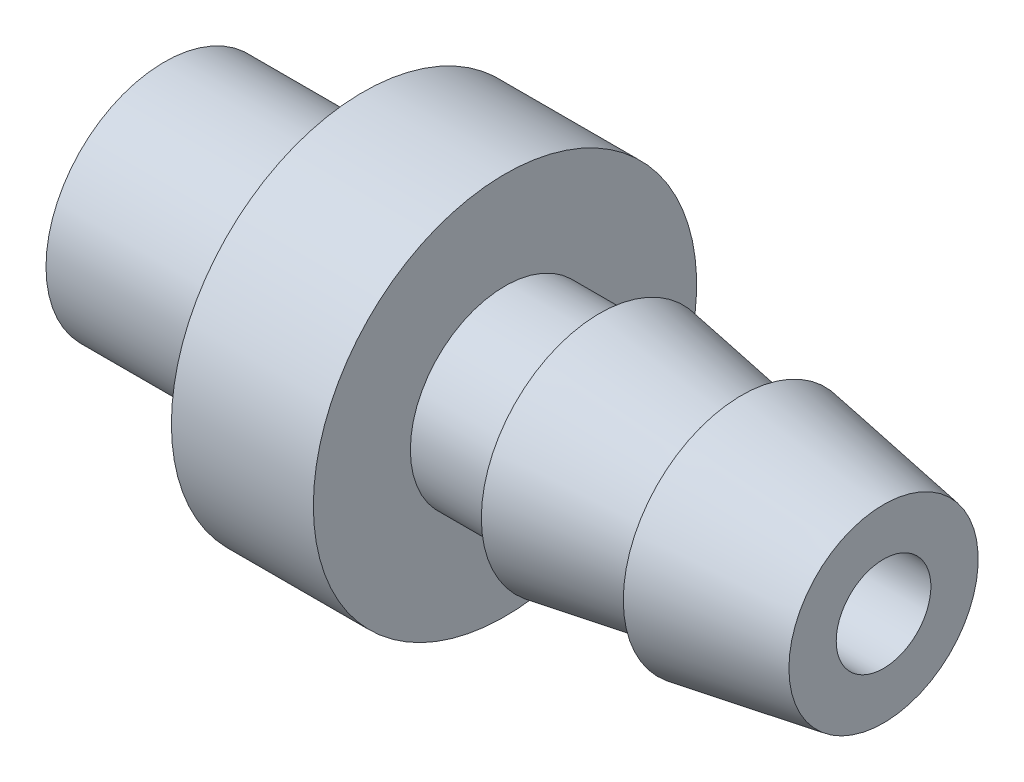
SolidWorks part; units mm, degrees
ref_plane "Front" through (0, 0, 0) normal (0, 0, 1) x (1, 0, 0)
ref_plane "Top" through (0, 0, 0) normal (0, 1, 0) x (1, 0, 0)
ref_plane "Right" through (0, 0, 0) normal (1, 0, 0) x (0, 0, -1)
sketch "Esquisse4" plane through (0, 0, 0) normal (0, 0, 1) x (1, 0, 0)
  line L0 (0, 0) -> (11, 0) construction
  line L2 (0, 1) -> (-4.2, 1)
  line L3 (11, 1) -> (11, 2)
  line L4 (11, 2) -> (8, 2.5)
  line L5 (8, 2.5) -> (8, 2)
  line L6 (8, 2) -> (5, 2.5)
  line L7 (5, 2.5) -> (5, 2)
  line L8 (5, 2) -> (3, 2)
  line L9 (3, 2) -> (3, 4.05)
  line L10 (3, 4.05) -> (0, 4.05)
  line L11 (0, 4.05) -> (0, 2.5)
  line L12 (0, 1) -> (11, 1)
  line L13 (-4.2, 1) -> (-4.2, 2.5)
  line L14 (-4.2, 2.5) -> (0, 2.5)
  dimension "D1" = 4
  dimension "D2" = 11
  dimension "D3" = 3
  dimension "D4" = 3
  dimension "D5" = 2
  dimension "D6" = 5
  dimension "D7" = 8.1
  dimension "D8" = 2.5
  dimension "D9" = 2
  dimension "D10" = 4.2
revolve "Révolution2" add sketch "Esquisse4" angle 360 about L0
